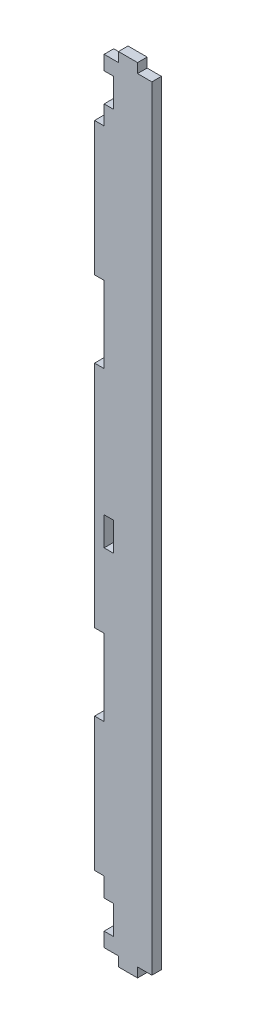
SolidWorks part; units mm, degrees
ref_plane "Front Plane" through (0, 0, 0) normal (0, 0, 1) x (1, 0, 0)
ref_plane "Top Plane" through (0, 0, 0) normal (0, 1, 0) x (1, 0, 0)
ref_plane "Right Plane" through (0, 0, 0) normal (1, 0, 0) x (0, 0, -1)
sketch "Sketch1" plane through (0, 0, 0) normal (0, 0, 1) x (1, 0, 0)
  line L0 (-439.375, -252.5) -> (-422.5, -252.5) construction
  line L6 (-440, -217.5) -> (-440, -177.5)
  line L7 (-440, -217.5) -> (-445, -217.5)
  line L8 (-422.5, -70) -> (-432.5, -70)
  line L9 (-432.5, -70) -> (-432.5, -75)
  line L11 (-422.5, -75) -> (-422.5, -70)
  line L19 (-485.1602, -277.5) -> (-382.7286, -277.5) construction
  line L20 (-422.5, -75) -> (-415, -75)
  line L23 (-432.5, -75) -> (-440, -75)
  line L26 (-440, -107.5) -> (-445, -107.5)
  line L27 (-445, -107.5) -> (-445, -177.5)
  line L28 (-440, -177.5) -> (-445, -177.5)
  line L29 (-440, -217.5) -> (-445, -217.5)
  line L30 (-414.9997, -302.5) -> (-414.9997, -302.4981)
  line L31 (-415, -75) -> (-415, -480)
  line L36 (-440, -107.5) -> (-440, -97.5)
  line L37 (-427.5, -70) -> (-427.5, -79.2087) construction
  line L38 (-440, -457.5) -> (-435, -457.5)
  line L39 (-415, -337.5) -> (-414.9997, -337.5)
  line L40 (-415, -447.5) -> (-414.9997, -447.5)
  line L41 (-432.5, -265.2975) -> (-432.5, -269.86) construction
  line L42 (-415, -377.5) -> (-414.9997, -377.5)
  line L45 (-415, -217.5) -> (-414.9997, -217.5)
  line L46 (-415, -177.5) -> (-414.9997, -177.5)
  line L48 (-415, -107.5) -> (-414.9997, -107.5)
  line L51 (-415, -217.5) -> (-414.9997, -217.5)
  line L52 (-435, -472.5) -> (-440, -472.5)
  line L53 (-435, -457.5) -> (-435, -472.5)
  line L54 (-414.9997, -252.5) -> (-414.9997, -252.5019)
  line L55 (-415, -337.5) -> (-414.9997, -337.5)
  line L56 (-440, -447.5) -> (-440, -457.5)
  line L57 (-440, -327.5) -> (-445, -327.5) [skipped]
  line L58 (-440, -337.5) -> (-445, -337.5)
  line L59 (-440, -377.5) -> (-445, -377.5)
  line L60 (-445, -447.5) -> (-445, -377.5)
  line L61 (-440, -447.5) -> (-445, -447.5)
  line L62 (-432.5, -480) -> (-440, -480)
  line L63 (-440, -82.5) -> (-435, -82.5)
  line L64 (-422.5, -480) -> (-415, -480)
  line L65 (-422.5, -480) -> (-422.5, -485)
  line L66 (-432.5, -485) -> (-432.5, -480)
  line L67 (-422.5, -485) -> (-432.5, -485)
  line L68 (-440, -337.5) -> (-445, -337.5)
  line L69 (-440, -337.5) -> (-440, -377.5)
  line L71 (-445, -217.5) -> (-445, -337.5)
  line L72 (-435, -97.5) -> (-440, -97.5)
  line L73 (-435, -82.5) -> (-435, -97.5)
  line L78 (-440, -283.75) -> (-435, -283.75)
  line L79 (-440, -298.75) -> (-440, -283.75)
  line L92 (-435, -298.75) -> (-440, -298.75)
  line L93 (-435, -283.75) -> (-435, -298.75)
  line L94 (-440, -472.5) -> (-440, -480)
  line L95 (-440, -82.5) -> (-440, -75)
  point P7 (-440, -252.5)
  point P47 (-415, -252.5)
  point P55 (-415, -302.5)
  point P56 (-440, -302.5)
  point P57 (-435, -283.75)
  point P60 (-440, -283.75)
  point P61 (-435, -298.75)
  point P62 (-440, -298.75)
  dimension "D1" = 25
  dimension "D2" = 7.5
  dimension "D3" = 5
  dimension "D4" = 35
  dimension "D6" = 2
  dimension "D7" = 2
extrude "Boss-Extrude1" add sketch "Sketch1" along normal blind 5
